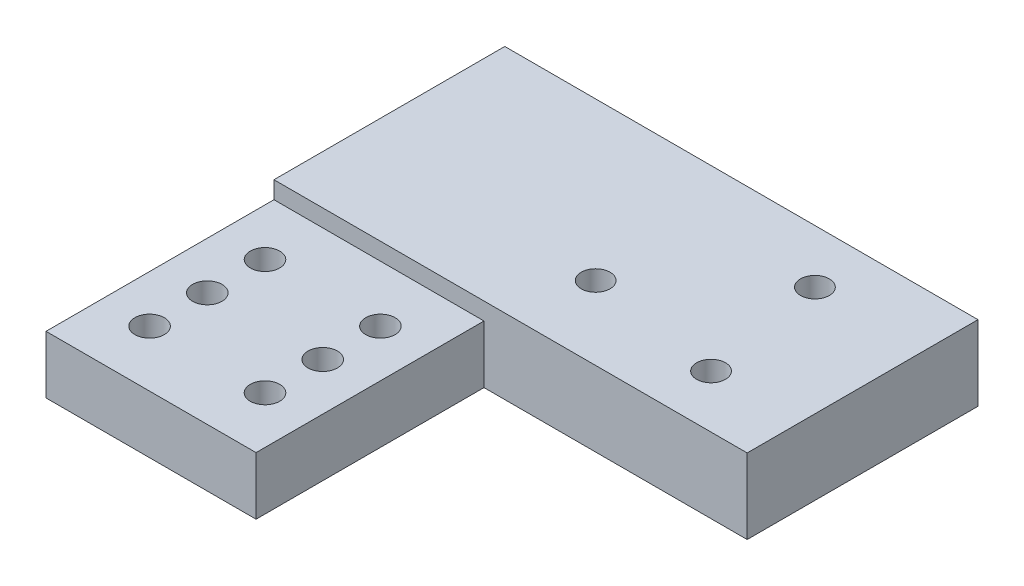
SolidWorks part; units mm, degrees
ref_plane "Front Plane" through (0, 0, 0) normal (0, 0, 1) x (1, 0, 0)
ref_plane "Top Plane" through (0, 0, 0) normal (0, 1, 0) x (1, 0, 0)
ref_plane "Right Plane" through (0, 0, 0) normal (1, 0, 0) x (0, 0, -1)
sketch "Sketch1" plane through (0, 0, 0) normal (0, 1, 0) x (1, 0, 0)
  line L1 (0, 0) -> (36.4, 0)
  line L2 (0, 0) -> (0, 39.5)
  line L3 (0, 39.5) -> (36.4, 39.5)
  line L4 (36.4, 0) -> (36.4, 39.5)
  circle A0 centre (8.2, 29.75) radius 2.55
  circle A1 centre (28.2, 29.75) radius 2.55
  circle A2 centre (28.2, 19.75) radius 2.55
  circle A3 centre (28.2, 9.75) radius 2.55
  circle A4 centre (8.2, 19.75) radius 2.55
  circle A5 centre (8.2, 9.75) radius 2.55
  dimension "D3" = 5.1
  dimension "D1" = 8.2
  dimension "D2" = 9.75
  dimension "D4" = 8.2
  dimension "D5" = 9.75
  dimension "D8" = 20
  dimension "D9" = 39.5
  dimension "D6" = 2
  dimension "D7" = 3
extrude "Boss-Extrude1" add sketch "Sketch1" along normal blind 10
sketch "Sketch2" plane through (0, 10, 0) normal (0, 1, 0) x (1, 0, 0)
  line L1 (0, 39.5) -> (82, 39.5)
  line L2 (0, 39.5) -> (0, 79.5)
  line L3 (0, 79.5) -> (82, 79.5)
  line L4 (82, 39.5) -> (82, 79.5)
  dimension "D1" = 82
  dimension "D2" = 40
extrude "Boss-Extrude2" add sketch "Sketch2" against normal blind 10 and the other way blind 3
sketch "Sketch4" plane through (0, 13, 0) normal (0, 1, 0) x (1, 0, 0)
  line L0 (66.5819, 48.6599) -> (66.5819, 39.5)
  line L2 (66.5819, 39.5) -> (82, 39.5)
  dimension "D1" = 9.1599
  dimension "D2" = 15.4181
  dimension "D3" = 0
  dimension "D4" = 0
  dimension "D5" = 15.4181
sketch "Sketch3" plane through (0, 13, 0) normal (0, 1, 0) x (1, 0, 0)
  line L7 (42.9961, 52.2457) -> (66.5819, 52.2457)
  line L8 (66.5819, 48.6599) -> (42.9961, 52.2457)
  line L9 (66.5819, 52.2457) -> (66.5819, 48.6599)
  line L10 (62.9961, 52.2457) -> (42.9961, 52.2457)
  line L11 (62.9961, 70.2457) -> (62.9961, 52.2457)
  line L12 (42.9961, 52.2457) -> (62.9961, 70.2457)
  dimension "D5" = 26.9072
  dimension "D1" = 18
  dimension "D2" = 3.5858
  dimension "D3" = 3.5858
  dimension "D4" = 23.5858
  dimension "D6" = 23.5858
  dimension "D7" = 23.8568
  dimension "D8" = 20
  dimension "D9" = 0
  dimension "D10" = 0
hole_wizard "Ø5.0mm Dowel Hole1" positions "3DSketch1" profile "Sketch5" hole size "Ø5.0" standard "ANSI Metric" end condition through all
sketch3d "3DSketch1"
  point P0 (42.9961, 13, -52.2457)
  point P3 (62.9961, 13, -70.2457)
  point P10 (66.5819, 13, -48.6599)
sketch "Sketch5" plane through (42.9961, 13, -52.2457) normal (1, 0, 0) x (0, 0, 1)
  line L0 (0, 0) -> (0, 13)
  line L1 (0, 13) -> (2.5, 13)
  line L2 (2.5, 13) -> (2.5, 0)
  line L5 (2.5, 0) -> (0, 0)
  line L11 (0, -6.35) -> (0, 107.95) construction
  dimension "Thru Hole Dia." = 5
  dimension "Thru Hole Depth" = 13
